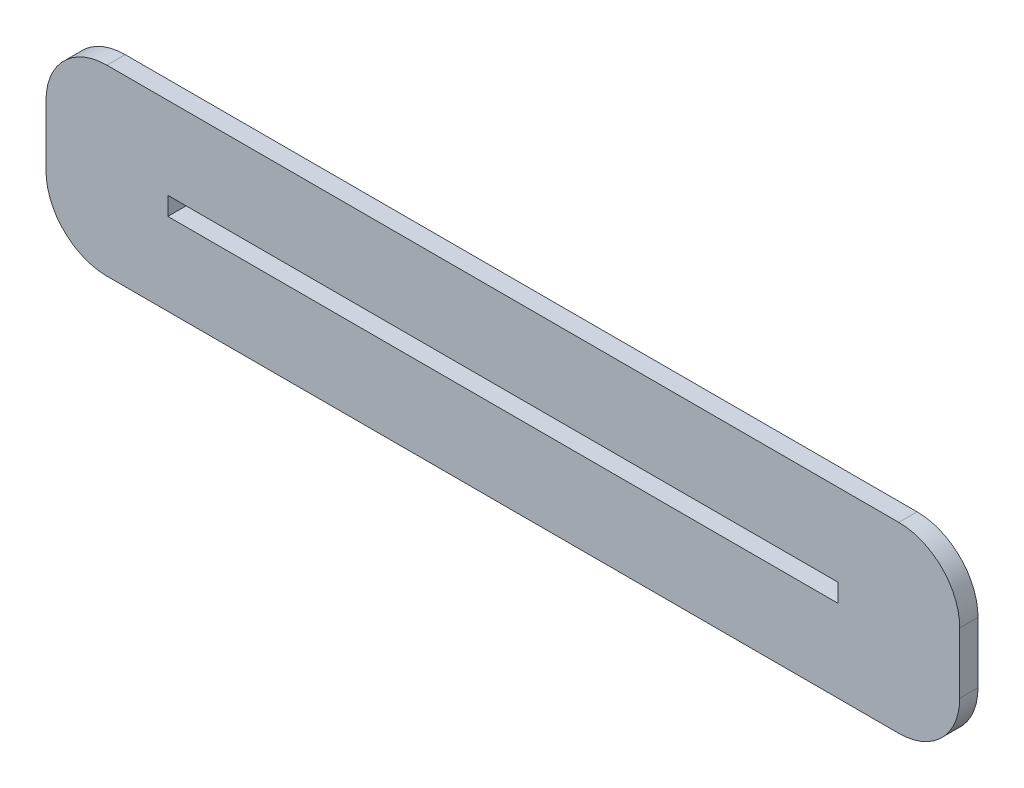
SolidWorks part; units mm, degrees
ref_plane "Front Plane" through (0, 0, 0) normal (0, 0, 1) x (1, 0, 0)
ref_plane "Top Plane" through (0, 0, 0) normal (0, 1, 0) x (1, 0, 0)
ref_plane "Right Plane" through (0, 0, 0) normal (1, 0, 0) x (0, 0, -1)
sketch "Sketch1" plane through (0, 0, 0) normal (0, 0, 1) x (1, 0, 0)
  line L0 (0, 15) -> (165.98, 15) construction
  line L1 (0, 0) -> (150, 0)
  line L2 (0, 0) -> (0, 30)
  line L3 (0, 30) -> (150, 30)
  line L4 (150, 0) -> (150, 30)
  line L6 (20, 13.5) -> (130, 13.5)
  line L7 (20, 13.5) -> (20, 16.5)
  line L8 (20, 16.5) -> (130, 16.5)
  line L9 (130, 13.5) -> (130, 16.5)
  line L10 (20, 13.5) -> (130, 16.5) construction
  line L11 (20, 16.5) -> (130, 13.5) construction
  point P7 (75, 15)
  dimension "D1" = 30
  dimension "D2" = 150
  dimension "D3" = 110
  dimension "D4" = 3
extrude "Boss-Extrude1" add sketch "Sketch1" along normal blind 3
fillet "Fillet1" radius 10 4 edges at (0, 30, 1.5) (0, 0, 1.5) (150, 0, 1.5) (150, 30, 1.5)
